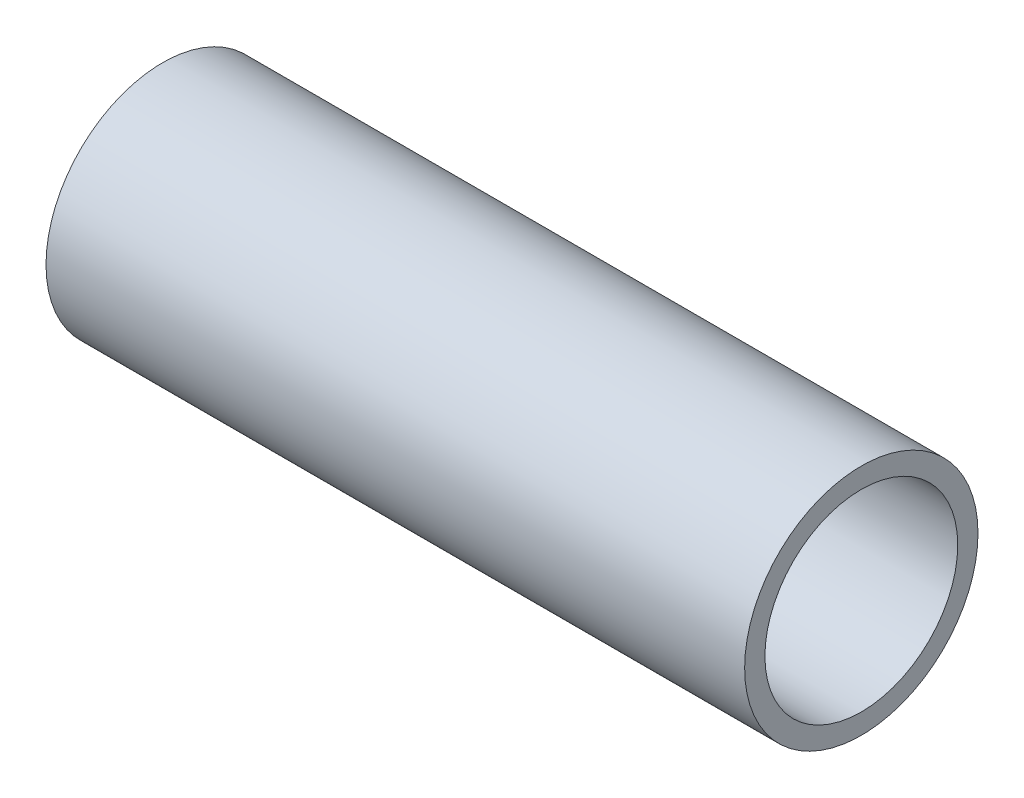
SolidWorks part; units mm, degrees
material "ASTM A106"
ref_plane "Front Plane" through (0, 0, 0) normal (0, 0, 1) x (1, 0, 0)
ref_plane "Top Plane" through (0, 0, 0) normal (0, 1, 0) x (1, 0, 0)
ref_plane "Right Plane" through (0, 0, 0) normal (1, 0, 0) x (0, 0, -1)
sketch "Sketch1" plane through (0, 0, 0) normal (1, 0, 0) x (0, 0, -1)
  circle A0 centre (0, 0) radius 16.7
  circle A1 centre (0, 0) radius 13.8
  dimension "D1" = 33.4
  dimension "D2" = 27.6
extrude "Boss-Extrude1" add sketch "Sketch1" along normal blind 100
